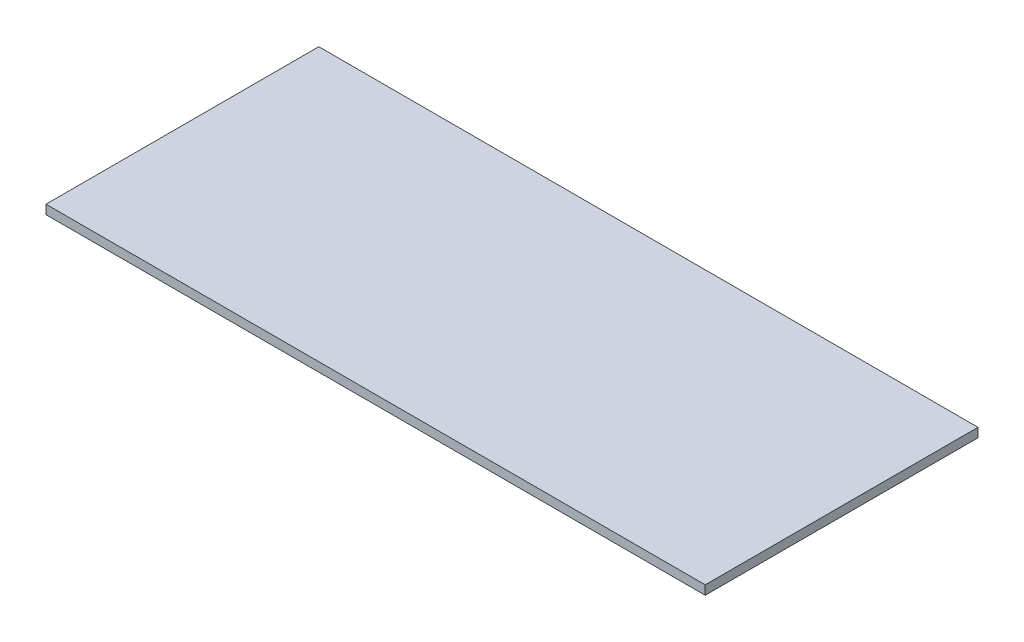
SolidWorks part; units mm, degrees
ref_plane "Front Plane" through (0, 0, 0) normal (0, 0, 1) x (1, 0, 0)
ref_plane "Top Plane" through (0, 0, 0) normal (0, 1, 0) x (1, 0, 0)
ref_plane "Right Plane" through (0, 0, 0) normal (1, 0, 0) x (0, 0, -1)
sketch "Sketch1" plane through (0, 0, 0) normal (0, 1, 0) x (1, 0, 0)
  line L1 (-72.5, 30) -> (72.5, 30)
  line L2 (-72.5, 30) -> (-72.5, -30)
  line L3 (-72.5, -30) -> (72.5, -30)
  line L4 (72.5, 30) -> (72.5, -30)
  line L5 (-72.5, 30) -> (72.5, -30) construction
  line L6 (-72.5, -30) -> (72.5, 30) construction
  point P0 (0, 0)
  dimension "D1" = 60
  dimension "D2" = 145
extrude "Boss-Extrude1" add sketch "Sketch1" along normal mid plane 2
